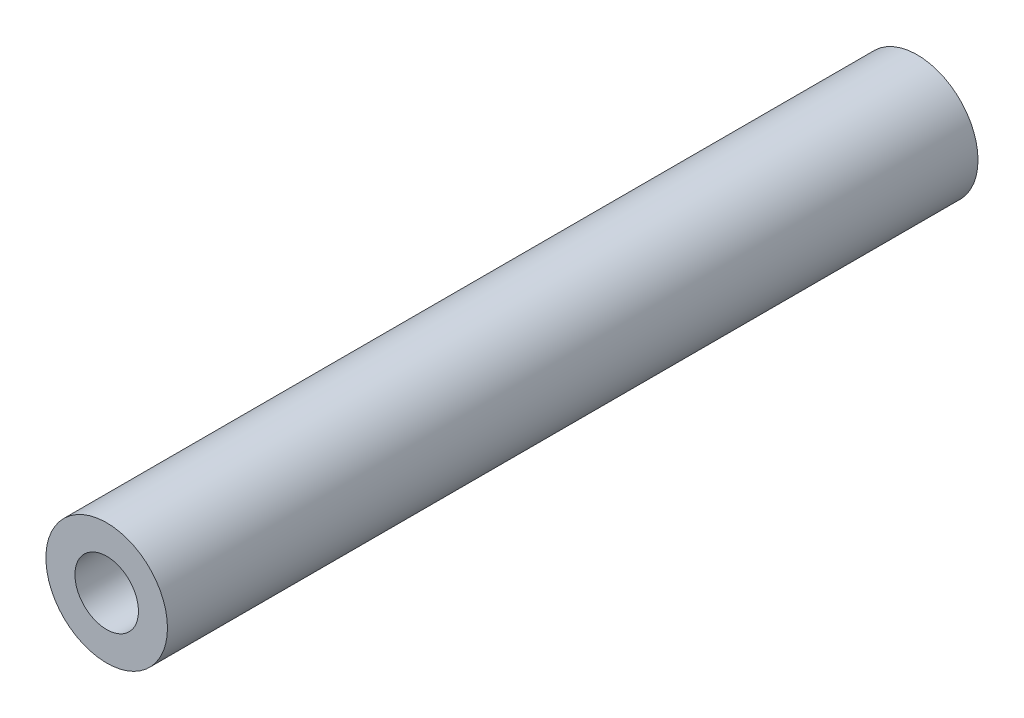
SolidWorks part; units mm, degrees
ref_plane "Front Plane" through (0, 0, 0) normal (0, 0, 1) x (1, 0, 0)
ref_plane "Top Plane" through (0, 0, 0) normal (0, 1, 0) x (1, 0, 0)
ref_plane "Right Plane" through (0, 0, 0) normal (1, 0, 0) x (0, 0, -1)
sketch "Sketch1" plane through (0, 0, 0) normal (0, 0, 1) x (1, 0, 0)
  circle A0 centre (0, 0) radius 2.4892
  circle A1 centre (0, 0) radius 4.7625
  dimension "D1" = 4.9784
  dimension "D2" = 9.525
extrude "Boss-Extrude1" add sketch "Sketch1" along normal mid plane 63.5 contours A0 | A1
